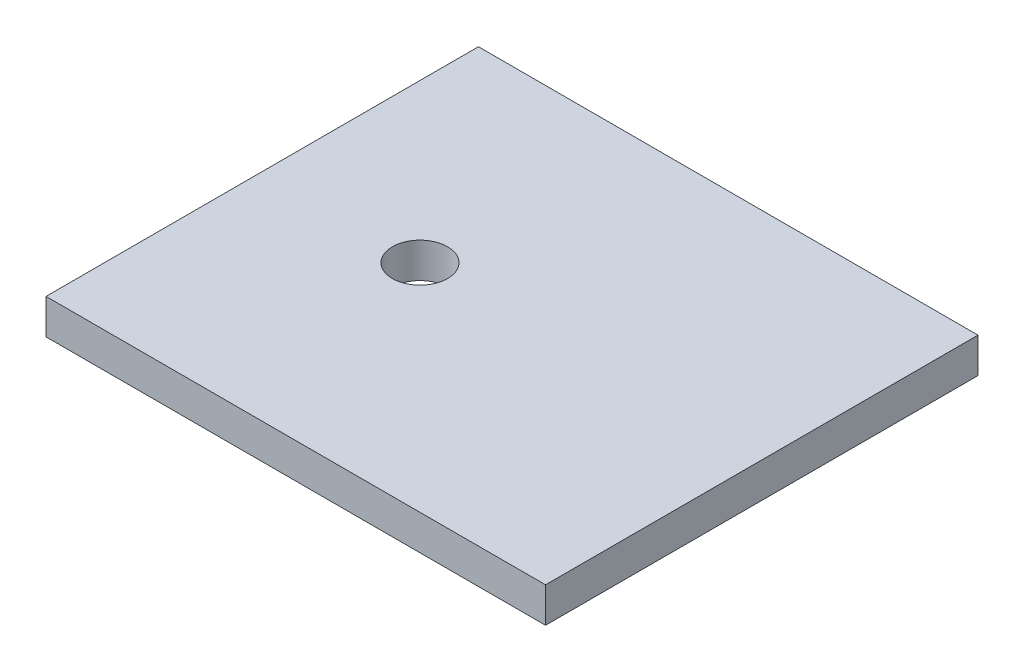
SolidWorks part; units mm, degrees
ref_plane "Front Plane" through (0, 0, 0) normal (0, 0, 1) x (1, 0, 0)
ref_plane "Top Plane" through (0, 0, 0) normal (0, 1, 0) x (1, 0, 0)
ref_plane "Right Plane" through (0, 0, 0) normal (1, 0, 0) x (0, 0, -1)
sketch "Sketch2" plane through (0, 0, 0) normal (0, 1, 0) x (1, 0, 0)
  line L1 (-85.725, -117.5) -> (85.725, -117.5)
  line L2 (-85.725, -117.5) -> (-85.725, 117.5)
  line L3 (-85.725, 117.5) -> (85.725, 117.5)
  line L4 (85.725, -117.5) -> (85.725, 117.5)
  line L5 (-85.725, -117.5) -> (85.725, 117.5) construction
  line L6 (-85.725, 117.5) -> (85.725, -117.5) construction
  circle A0 centre (0, 0) radius 15
  point P0 (0, 0)
  dimension "D2" = 30
  dimension "D1" = 235
extrude "Boss-Extrude3" add sketch "Sketch2" along normal blind 19.05
sketch "Sketch3" plane through (85.725, 0, 0) normal (1, 0, 0) x (0, 0, -1)
  line L1 (-117.5, 0) -> (117.5, 0)
  line L2 (-117.5, 0) -> (-117.5, 19.05)
  line L3 (-117.5, 19.05) -> (117.5, 19.05)
  line L4 (117.5, 0) -> (117.5, 19.05)
extrude "Boss-Extrude4" add sketch "Sketch3" along normal blind 100
